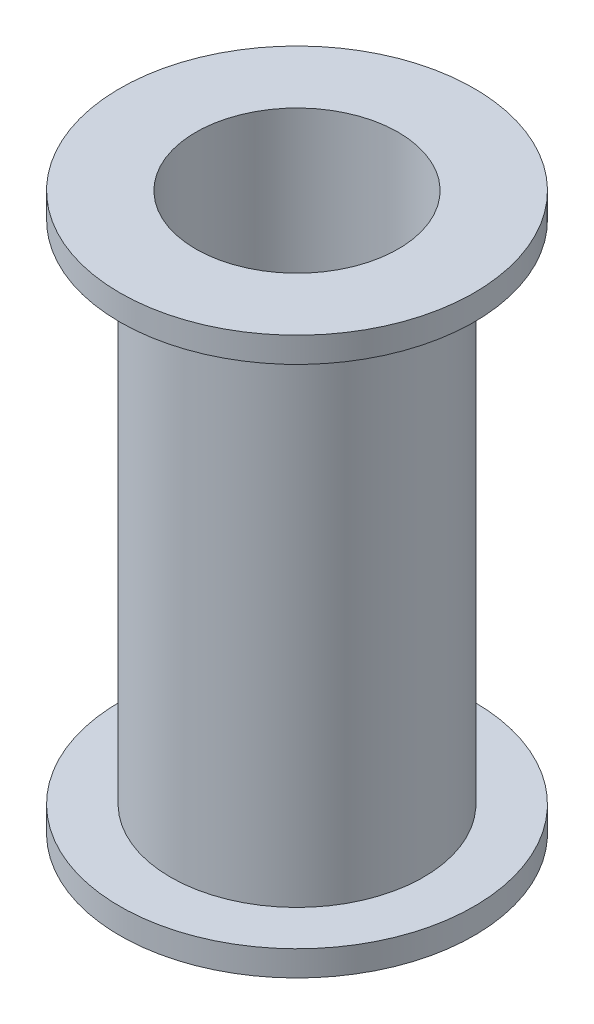
SolidWorks part; units mm, degrees
ref_plane "Plano frontal" through (0, 0, 0) normal (0, 0, 1) x (1, 0, 0)
ref_plane "Plano superior" through (0, 0, 0) normal (0, 1, 0) x (1, 0, 0)
ref_plane "Plano direito" through (0, 0, 0) normal (1, 0, 0) x (0, 0, -1)
sketch "Esboço1" plane through (0, 0, 0) normal (0, 1, 0) x (1, 0, 0)
  circle A1 centre (0, 0) radius 50
  point P3 (0, 0)
extrude "Ressalto-extrusão2" add sketch "Esboço1" along normal blind 200
sketch "Esboço5" plane through (0, 200, 0) normal (0, 1, 0) x (1, 0, 0)
  circle A0 centre (0, 0) radius 70
extrude "Ressalto-extrusão3" add sketch "Esboço5" along normal blind 10
sketch "Esboço6" plane through (0, 0, 0) normal (0, -1, 0) x (-1, 0, 0)
  circle A0 centre (0, 0) radius 70
extrude "Ressalto-extrusão4" add sketch "Esboço6" along normal blind 10
sketch "Esboço7" plane through (0, -10, 0) normal (0, -1, 0) x (-1, 0, 0)
  circle A0 centre (0, 0) radius 40
extrude "Corte-extrusão3" cut sketch "Esboço7" against normal blind 220
